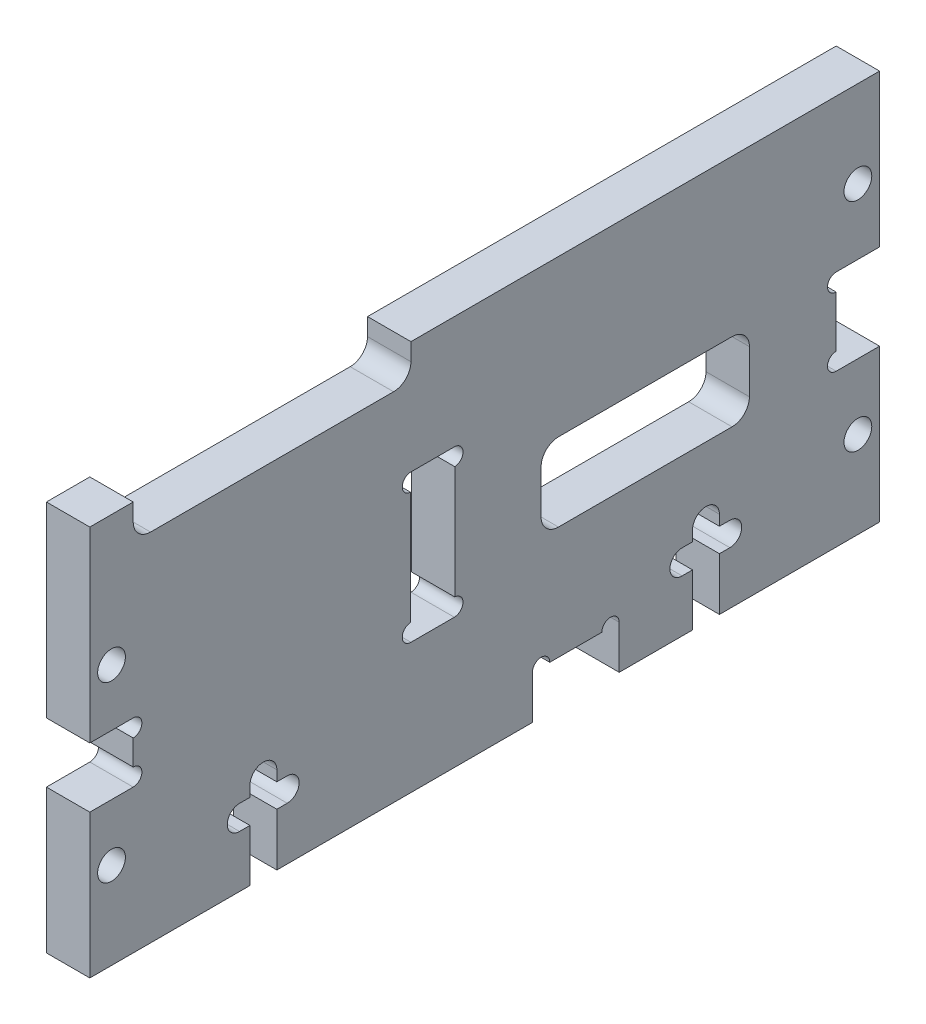
SolidWorks part; units mm, degrees
ref_plane "정면" through (0, 0, 0) normal (0, 0, 1) x (1, 0, 0)
ref_plane "윗면" through (0, 0, 0) normal (0, 1, 0) x (1, 0, 0)
ref_plane "우측면" through (0, 0, 0) normal (1, 0, 0) x (0, 0, -1)
sketch "스케치1" plane through (0, 0, 0) normal (1, 0, 0) x (0, 0, -1)
  line L1 (0, 0) -> (91, 0)
  line L2 (0, 0) -> (0, 45)
  line L3 (0, 45) -> (91, 45)
  line L4 (91, 0) -> (91, 45)
  dimension "D1" = 45
  dimension "D2" = 91
extrude "보스-돌출1" add sketch "스케치1" along normal blind 5
sketch "스케치2" plane through (5, 0, 0) normal (1, 0, 0) x (0, 0, -1)
  line L0 (0, 45) -> (0, 0) construction
  line L1 (0, 41) -> (5, 41)
  line L2 (0, 41) -> (0, 31)
  line L3 (0, 31) -> (5, 31)
  line L4 (5, 41) -> (5, 31)
  line L5 (91, 0) -> (91, 45) construction
  line L6 (0, 19) -> (5, 19)
  line L7 (0, 19) -> (0, 9)
  line L8 (0, 9) -> (5, 9)
  line L9 (5, 19) -> (5, 9)
  line L10 (37, 41) -> (42, 41)
  line L11 (37, 41) -> (37, 31)
  line L12 (37, 31) -> (42, 31)
  line L13 (42, 41) -> (42, 31)
  line L14 (37, 19) -> (42, 19)
  line L15 (37, 19) -> (37, 9)
  line L16 (37, 9) -> (42, 9)
  line L17 (42, 19) -> (42, 9)
  line L18 (86, 41) -> (91, 41)
  line L19 (86, 41) -> (86, 31)
  line L20 (86, 31) -> (91, 31)
  line L21 (91, 41) -> (91, 31)
  line L22 (5, 31) -> (37, 31) construction
  line L23 (86, 19) -> (91, 19)
  line L24 (86, 19) -> (86, 9)
  line L25 (86, 9) -> (91, 9)
  line L26 (91, 19) -> (91, 9)
  line L27 (37, 19) -> (37, 31) construction
  line L28 (5, 19) -> (5, 31) construction
  line L29 (37, 41) -> (5, 41) construction
  line L30 (42, 41) -> (86, 41) construction
  line L31 (86, 31) -> (86, 19) construction
  line L32 (42, 31) -> (42, 19) construction
  line L33 (42, 19) -> (86, 19) construction
  line L34 (86, 31) -> (42, 31) construction
  line L35 (42, 9) -> (86, 9) construction
  line L36 (37, 19) -> (5, 19) construction
  line L37 (5, 9) -> (37, 9) construction
  line L38 (91, 45) -> (0, 45) construction
  dimension "D1" = 5
  dimension "D2" = 5
  dimension "D3" = 5
  dimension "D4" = 10
  dimension "D5" = 10
  dimension "D6" = 12
  dimension "D7" = 4
  dimension "D8" = 32
extrude "컷-돌출1" [suppressed] cut sketch "스케치2" against normal blind 5
sketch "스케치3" [suppressed] plane through (5, 0, 0) normal (1, 0, 0) x (0, 0, -1)
  line L0 (91, 36) -> (86, 36) construction
  line L1 (86, 26) -> (91, 26) construction
  line L2 (91, 14) -> (86, 14) construction
  line L3 (86, 4) -> (91, 4) construction
  line L4 (42, 4) -> (42, 14) construction
  line L5 (37, 14) -> (37, 4) construction
  line L6 (37, 36) -> (37, 26) construction
  line L7 (42, 26) -> (42, 36) construction
  line L9 (5, 14) -> (0, 14) construction
  line L10 (0, 26) -> (5, 26) construction
  line L11 (5, 36) -> (0, 36) construction
  line L12 (0, 4) -> (5, 4) construction
  circle A0 centre (87, 36) radius 1
  circle A1 centre (87, 26) radius 1
  circle A2 centre (87, 14) radius 1
  circle A3 centre (87, 4) radius 1
  circle A4 centre (42, 13) radius 1
  circle A5 centre (37, 13) radius 1
  circle A6 centre (37, 27) radius 1
  circle A7 centre (42, 27) radius 1
  circle A8 centre (42, 35) radius 1
  circle A9 centre (37, 35) radius 1
  circle A10 centre (37, 5) radius 1
  circle A11 centre (42, 5) radius 1
  circle A12 centre (4, 14) radius 1
  circle A13 centre (4, 26) radius 1
  circle A14 centre (4, 36) radius 1
  circle A15 centre (4, 4) radius 1
  dimension "D1" = 2
extrude "컷-돌출2" [suppressed] cut sketch "스케치3" against normal blind 5
sketch "스케치7" plane through (5, 0, 0) normal (1, 0, 0) x (0, 0, -1)
  line L0 (86, 36.55) -> (86, 52) construction
  line L1 (52, 27) -> (76, 27)
  line L2 (52, 27) -> (52, 18)
  line L3 (52, 18) -> (76, 18)
  line L4 (76, 27) -> (76, 18)
  line L5 (42, 34) -> (42, 52) construction
  line L6 (91, 45) -> (0, 45) construction
  line L7 (0, 0) -> (91, 0) construction
  dimension "D1" = 10
  dimension "D2" = 10
  dimension "D3" = 18
  dimension "D4" = 18
extrude "컷-돌출3" cut sketch "스케치7" against normal blind 10
fillet "필렛1" radius 2 4 edges at (2.5, 18, -52) (2.5, 18, -76) (2.5, 27, -76) (2.5, 27, -52)
sketch "스케치8" plane through (5, 0, 0) normal (1, 0, 0) x (0, 0, -1)
  line L0 (91, 45) -> (0, 45) construction
  line L1 (5, 45) -> (37, 45)
  line L2 (5, 45) -> (5, 41)
  line L3 (5, 41) -> (37, 41)
  line L4 (37, 45) -> (37, 41)
  line L5 (5, 31.55) -> (5, 52) construction
  line L6 (37, 34) -> (37, 52) construction
  dimension "D1" = 4
extrude "컷-돌출4" cut sketch "스케치8" against normal blind 10
fillet "필렛2" radius 2 2 edges at (2.5, 41, -37) (2.5, 41, -5)
sketch "스케치9" plane through (0, 0, 0) normal (-1, 0, 0) x (0, 0, 1)
  line L1 (-42, 32) -> (-37, 32)
  line L2 (-42, 32) -> (-42, 15)
  line L3 (-42, 15) -> (-37, 15)
  line L4 (-37, 32) -> (-37, 15)
extrude "컷-돌출5" cut sketch "스케치9" against normal blind 5
sketch "스케치10" plane through (5, 0, 0) normal (1, 0, 0) x (0, 0, -1)
  line L0 (42, 32) -> (42, 15) construction
  line L1 (37, 15) -> (37, 32) construction
  circle A0 centre (42, 31) radius 1
  circle A1 centre (42, 16) radius 1
  circle A2 centre (37, 16) radius 1
  circle A3 centre (37, 31) radius 1
  dimension "D1" = 2
sketch "스케치14" plane through (5, 0, 0) normal (1, 0, 0) x (0, 0, -1)
  line L0 (88.5, 36.55) -> (88.5, 33.585) construction
  line L1 (86, 36.55) -> (91, 36.55) construction
  line L2 (88.5, 11.55) -> (88.5, 8.45) construction
  line L3 (86, 11.55) -> (91, 11.55) construction
  line L4 (86, 8.45) -> (91, 8.45) construction
  line L5 (2.5, 31.55) -> (2.5, 28.45) construction
  line L6 (5, 31.55) -> (0, 31.55) construction
  line L7 (5, 28.45) -> (0, 28.45) construction
  line L8 (2.5, 11.55) -> (2.5, 8.45) construction
  line L9 (5, 11.55) -> (0, 11.55) construction
  line L10 (5, 8.45) -> (0, 8.45) construction
  circle A0 centre (2.5, 10) radius 1.55
  circle A1 centre (2.5, 30) radius 1.55
  circle A2 centre (88.5, 35.0675) radius 1.4825
  circle A3 centre (88.5, 10) radius 1.55
extrude "컷-돌출9" cut sketch "스케치14" against normal blind 10
extrude "컷-돌출6" cut sketch "스케치10" against normal blind 10
sketch "스케치12" plane through (5, 0, 0) normal (1, 0, 0) x (0, 0, -1)
  line L0 (88.5, 35) -> (88.5, 10) construction
  line L1 (2.5, 30) -> (2.5, 10) construction
  line L2 (91, 0) -> (91, 45) construction
  line L3 (91, 45) -> (37, 45) construction
  line L4 (0, 45) -> (0, 0) construction
  line L5 (0, 0) -> (91, 0) construction
  circle A0 centre (2.5, 30) radius 1.6
  circle A1 centre (2.5, 10) radius 1.6
  circle A2 centre (88.5, 35) radius 1.6
  circle A3 centre (88.5, 10) radius 1.6
  dimension "D3" = 3.2
  dimension "D1" = 2.5
  dimension "D2" = 25
  dimension "D4" = 10
  dimension "D5" = 2.5
  dimension "D6" = 20
  dimension "D7" = 10
extrude "컷-돌출7" cut sketch "스케치12" against normal blind 10
sketch "스케치13" plane through (5, 0, 0) normal (1, 0, 0) x (0, 0, -1)
  line L0 (18.45, 0) -> (18.45, 6)
  line L1 (18.45, 0) -> (21.55, 0)
  line L2 (21.55, 0) -> (21.55, 6.0651)
  line L3 (18.45, 10) -> (21.55, 10) construction
  line L4 (21.55, 8.7999) -> (21.55, 10)
  line L5 (18.45, 6) -> (17.2502, 6)
  line L6 (17.2502, 6) -> (17.2325, 8.7999) construction
  line L7 (17.2325, 8.7999) -> (18.45, 8.7999)
  line L8 (21.55, 8.7999) -> (22.7498, 8.7999)
  line L9 (22.7498, 8.7999) -> (22.7498, 6.0651) construction
  line L10 (18.45, 8.7999) -> (18.45, 10)
  line L11 (22.7498, 6.0651) -> (21.55, 6.0651)
  line L12 (18.45, 6) -> (21.55, 6.0651) construction
  line L13 (18.45, 8.7999) -> (21.55, 8.7999) construction
  line L14 (21.55, 6.0651) -> (21.55, 8.7999) construction
  line L15 (18.45, 8.7999) -> (18.45, 6) construction
  line L16 (20, 10) -> (20, 16.1272) construction
  line L17 (0, 45) -> (0, 0) construction
  line L18 (72.55, 0) -> (72.55, 6.0651)
  line L19 (69.45, 10) -> (72.55, 10) construction
  line L20 (68.2502, 6) -> (68.2325, 8.7999) construction
  line L21 (72.55, 6.0651) -> (72.55, 8.7999) construction
  line L22 (69.45, 0) -> (72.55, 0)
  line L23 (68.2325, 8.7999) -> (69.45, 8.7999)
  line L24 (69.45, 0) -> (69.45, 6)
  line L25 (73.7498, 8.7999) -> (73.7498, 6.0651) construction
  line L26 (69.45, 6) -> (68.2502, 6)
  line L27 (69.45, 8.7999) -> (69.45, 6) construction
  line L28 (72.55, 8.7999) -> (72.55, 10)
  line L29 (69.45, 6) -> (72.55, 6.0651) construction
  line L30 (69.45, 8.7999) -> (72.55, 8.7999) construction
  line L31 (72.55, 8.7999) -> (73.7498, 8.7999)
  line L32 (69.45, 8.7999) -> (69.45, 10)
  line L33 (71, 10) -> (71, 16.1272) construction
  line L34 (73.7498, 6.0651) -> (72.55, 6.0651)
  line L35 (91, 0) -> (91, 45) construction
  arc A0 (17.2325, 8.7999) -> (17.2502, 6) centre (17.2414, 7.4) ccw
  arc A1 (22.7498, 6.0651) -> (22.7498, 8.7999) centre (22.7498, 7.4325) ccw
  arc A2 (21.55, 10) -> (18.45, 10) centre (20, 10) ccw
  arc A3 (72.55, 10) -> (69.45, 10) centre (71, 10) ccw
  arc A4 (68.2325, 8.7999) -> (68.2502, 6) centre (68.2414, 7.4) ccw
  arc A5 (73.7498, 6.0651) -> (73.7498, 8.7999) centre (73.7498, 7.4325) ccw
  dimension "D1" = 3.1
  dimension "D2" = 10
  dimension "D3" = 5.5
  dimension "D4" = 2.8
  dimension "D5" = 20
  dimension "D6" = 6
  dimension "D7" = 3.1
  dimension "D8" = 10
  dimension "D9" = 5.5
  dimension "D10" = 2.8
  dimension "D11" = 6
  dimension "D12" = 20
extrude "컷-돌출8" cut sketch "스케치13" against normal blind 10
sketch "스케치15" plane through (5, 0, 0) normal (1, 0, 0) x (0, 0, -1)
  line L0 (21.55, 0) -> (69.45, 0) construction
  line L1 (51, 5) -> (61, 5)
  line L2 (51, 5) -> (51, 0)
  line L3 (51, 0) -> (61, 0)
  line L4 (61, 5) -> (61, 0)
  line L5 (61, 5) -> (61, 0) construction
extrude "컷-돌출10" cut sketch "스케치15" against normal blind 10
sketch "스케치19" plane through (0, 0, 0) normal (-1, 0, 0) x (0, 0, 1)
  line L0 (0, 45) -> (0, 0) construction
  line L1 (-5, 23.45) -> (0, 23.45)
  line L2 (-5, 23.45) -> (-5, 16.55)
  line L3 (-5, 16.55) -> (0, 16.55)
  line L4 (0, 23.45) -> (0, 16.55)
  line L5 (-5, 16.55) -> (0, 16.55) construction
  line L6 (-86, 17.55) -> (-91, 17.55) construction
  line L7 (-86, 27.45) -> (-91, 27.45)
  line L8 (-86, 27.45) -> (-86, 17.55)
  line L9 (-86, 17.55) -> (-91, 17.55)
  line L10 (-91, 27.45) -> (-91, 17.55)
  line L11 (-91, 0) -> (-91, 45) construction
extrude "컷-돌출14" cut sketch "스케치19" against normal blind 5
sketch "스케치16" plane through (0, 0, 0) normal (-1, 0, 0) x (0, 0, 1)
  line L0 (-51, 5) -> (-61, 5) construction
  line L1 (-86, 17.55) -> (-86, 27.45) construction
  line L2 (-5, 23.45) -> (-5, 16.55) construction
  circle A0 centre (-60, 5) radius 1
  circle A1 centre (-52, 5) radius 1
  circle A2 centre (-86, 26.45) radius 1
  circle A3 centre (-86, 18.55) radius 1
  circle A4 centre (-5, 22.45) radius 1
  circle A5 centre (-5, 17.55) radius 1
  dimension "D1" = 2
extrude "컷-돌출11" cut sketch "스케치16" against normal blind 10
sketch "스케치20" plane through (5, 0, 0) normal (1, 0, 0) x (0, 0, -1)
  line L0 (42, 30) -> (42, 17) construction
  line L1 (36.95, 31.1977) -> (42.05, 31.1977)
  line L2 (36.95, 31.1977) -> (36.95, 16)
  line L3 (36.95, 16) -> (42.05, 16)
  line L4 (42.05, 31.1977) -> (42.05, 16)
  line L5 (37, 17) -> (37, 30) construction
  dimension "D1" = 0.05
  dimension "D2" = 0.05
extrude "컷-돌출15" cut sketch "스케치20" against normal blind 10
